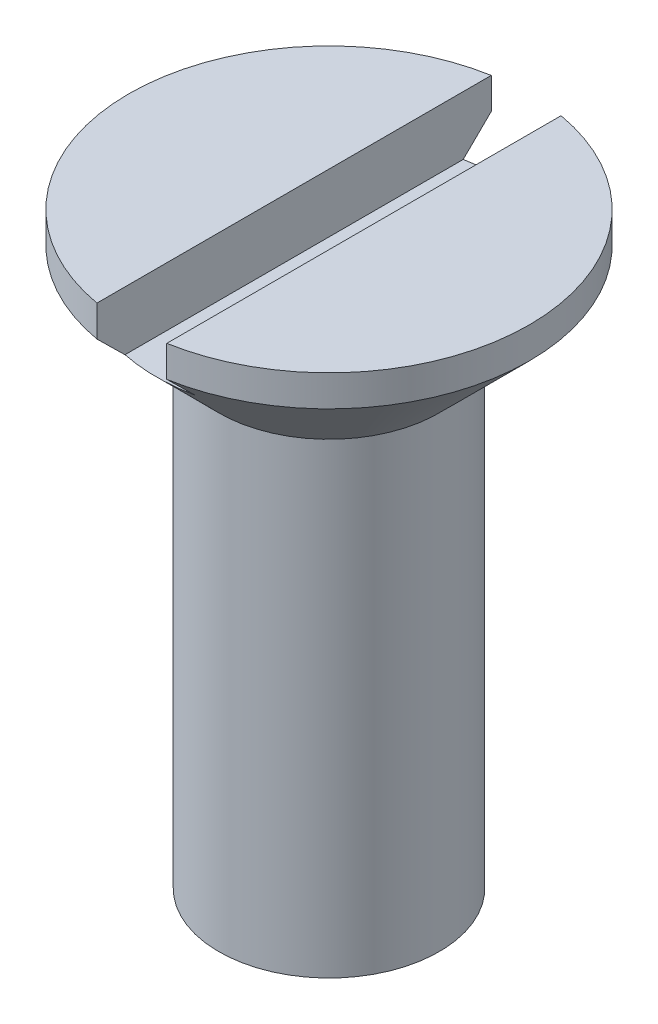
SolidWorks part; units mm, degrees
ref_plane "Front Plane" through (0, 0, 0) normal (0, 0, 1) x (1, 0, 0)
ref_plane "Top Plane" through (0, 0, 0) normal (0, 1, 0) x (1, 0, 0)
ref_plane "Right Plane" through (0, 0, 0) normal (1, 0, 0) x (0, 0, -1)
sketch "Sketch1" plane through (0, 0, 0) normal (0, 0, 1) x (1, 0, 0)
  line L0 (0, 0) -> (0, 16) construction
  line L1 (0, 16) -> (-5.45, 16)
  line L2 (-5.45, 16) -> (-5.45, 15.15)
  line L3 (-5.45, 15.15) -> (-3, 12.7)
  line L4 (-3, 12.7) -> (-3, 0)
  line L5 (0, -1.7321) -> (0, 0) construction
  line L6 (-3, 0) -> (0, -1.7321)
  line L7 (0, 16) -> (0, -1.7321)
  point P3 (0, 0)
  dimension "D1" = 10.9
  dimension "D2" = 16
  dimension "D3" = 3
  dimension "D4" = 3.3
  dimension "D5" = 45
  dimension "D6" = 60
revolve "Revolve1" add sketch "Sketch1" angle 360 about L7
sketch "Sketch2" plane through (0, 0, 0) normal (0, 0, 1) x (1, 0, 0)
  line L0 (5.45, 16) -> (-5.45, 16) construction
  line L1 (-0.95, 16) -> (0.95, 16)
  line L2 (-0.95, 16) -> (-0.95, 14.4)
  line L3 (-0.95, 14.4) -> (0.95, 14.4)
  line L4 (0.95, 16) -> (0.95, 14.4)
  point P6 (0, 16)
  dimension "D1" = 1.9
  dimension "D2" = 1.6
extrude "Cut-Extrude1" cut sketch "Sketch2" against normal through all both and the other way through all
